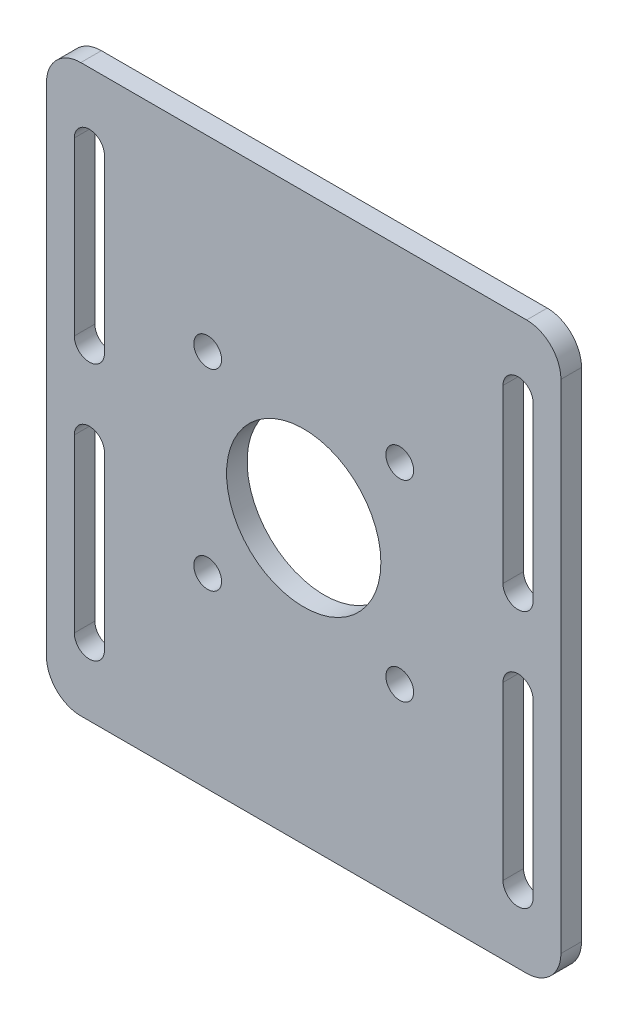
SolidWorks part; units mm, degrees
material "AISI 304"
ref_plane "Спереди" through (0, 0, 0) normal (0, 0, 1) x (1, 0, 0)
ref_plane "Сверху" through (0, 0, 0) normal (0, 1, 0) x (1, 0, 0)
ref_plane "Справа" through (0, 0, 0) normal (1, 0, 0) x (0, 0, -1)
sketch "Эскиз1" plane through (0, 0, 0) normal (0, 0, 1) x (1, 0, 0)
  line L1 (-150, -165) -> (150, -165)
  line L2 (-150, -165) -> (-150, 165)
  line L3 (-150, 165) -> (150, 165)
  line L4 (150, -165) -> (150, 165)
  line L5 (-150, -165) -> (150, 165) construction
  line L6 (-150, 165) -> (150, -165) construction
  circle A0 centre (0, 0) radius 45
  point P0 (0, 0)
  dimension "D3" = 90
  dimension "D1" = 300
  dimension "D2" = 330
extrude "Бобышка-Вытянуть1" add sketch "Эскиз1" along normal mid plane 12
fillet "Скругление1" radius 20 4 edges at (150, -165, 0) (-150, -165, 0) (150, 165, 0) (-150, 165, 0)
sketch "Эскиз3" plane through (0, 0, 6) normal (0, 0, 1) x (1, 0, 0)
  line L1 (-56, -56) -> (56, -56) construction
  line L2 (-56, -56) -> (-56, 56) construction
  line L3 (-56, 56) -> (56, 56) construction
  line L4 (56, -56) -> (56, 56) construction
  line L5 (-56, -56) -> (56, 56) construction
  line L6 (-56, 56) -> (56, -56) construction
  circle A0 centre (-56, 56) radius 8.1
  circle A1 centre (56, 56) radius 8.1
  circle A2 centre (56, -56) radius 8.1
  circle A3 centre (-56, -56) radius 8.1
  point P0 (0, 0)
  dimension "D2" = 16.2
  dimension "D1" = 112
extrude "Вырез-Вытянуть2" cut sketch "Эскиз3" against normal up to surface (12 mm away) up to face at (0, 0, -6)
sketch "Эскиз4" plane through (0, 0, -6) normal (0, 0, -1) x (-1, 0, 0)
  line L0 (-125, 25) -> (-125, 125) construction
  line L1 (-133.8, 25) -> (-133.8, 125)
  line L2 (-116.2, 25) -> (-116.2, 125)
  line L3 (0, 0) -> (0, 165) construction
  line L6 (0, 0) -> (-150, 0) construction
  line L7 (-150, -145) -> (-150, 145) construction
  line L8 (-130, 165) -> (130, 165) construction
  line L9 (6.6, 0) -> (-6.6, 0) construction
  line L10 (-125, -25) -> (-125, -125) construction
  line L11 (-133.8, -25) -> (-133.8, -125)
  line L12 (-116.2, -25) -> (-116.2, -125)
  line L13 (0, 6.6) -> (0, -6.6) construction
  line L14 (125, -25) -> (125, -125) construction
  line L15 (133.8, -25) -> (133.8, -125)
  line L16 (116.2, -25) -> (116.2, -125)
  line L17 (125, 25) -> (125, 125) construction
  line L18 (133.8, 25) -> (133.8, 125)
  line L19 (116.2, 25) -> (116.2, 125)
  arc A0 (-133.8, 25) -> (-116.2, 25) centre (-125, 25) ccw
  arc A1 (-116.2, 125) -> (-133.8, 125) centre (-125, 125) ccw
  arc A2 (-133.8, -25) -> (-116.2, -25) centre (-125, -25) cw
  arc A3 (-116.2, -125) -> (-133.8, -125) centre (-125, -125) cw
  arc A4 (133.8, -25) -> (116.2, -25) centre (125, -25) ccw
  arc A5 (116.2, -125) -> (133.8, -125) centre (125, -125) ccw
  arc A6 (133.8, 25) -> (116.2, 25) centre (125, 25) cw
  arc A7 (116.2, 125) -> (133.8, 125) centre (125, 125) cw
  point P2 (-125, 75)
  point P14 (-125, -75)
  point P28 (125, -75)
  point P35 (125, 75)
  dimension "D1" = 17.6
  dimension "D2" = 100
  dimension "D3" = 75
  dimension "D4" = 125
extrude "Вырез-Вытянуть3" cut sketch "Эскиз4" against normal up to surface (12 mm away) up to face at (-47.9, -56, 6)
